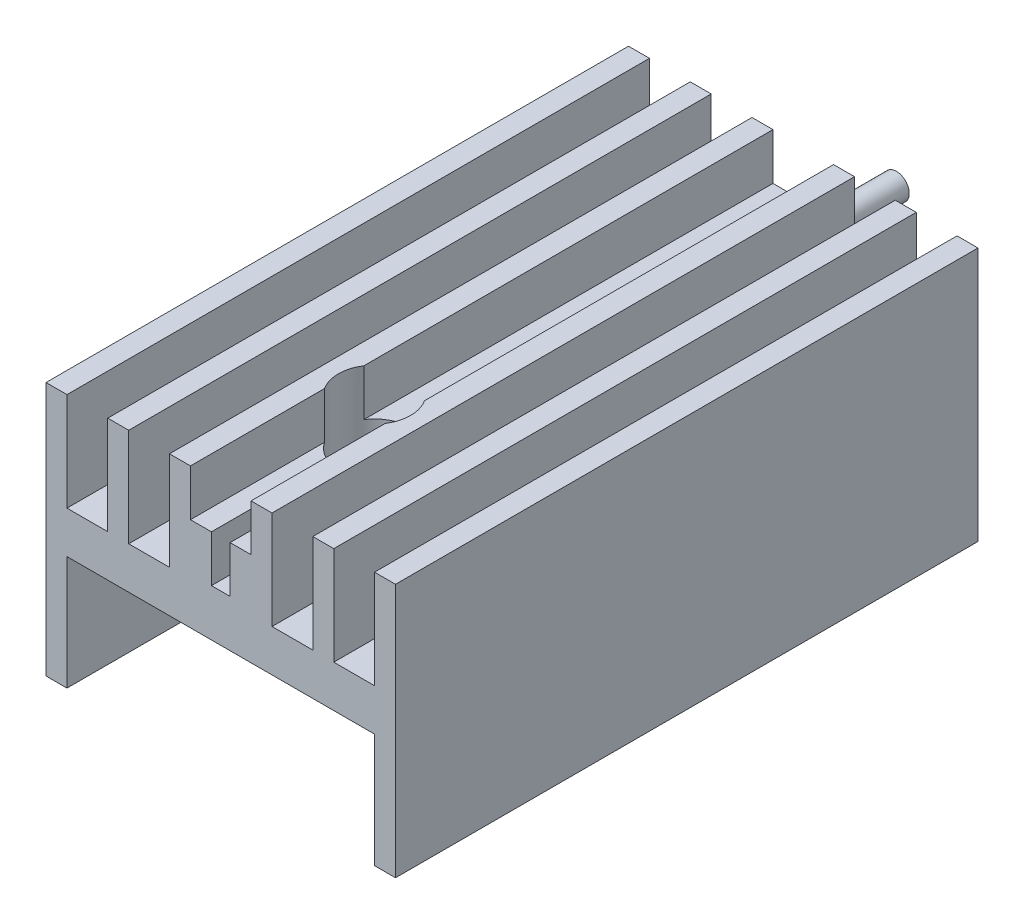
SolidWorks part; units mm, degrees
ref_plane "Front Plane" through (0, 0, 0) normal (0, 0, 1) x (1, 0, 0)
ref_plane "Top Plane" through (0, 0, 0) normal (0, 1, 0) x (1, 0, 0)
ref_plane "Right Plane" through (0, 0, 0) normal (1, 0, 0) x (0, 0, -1)
sketch "Sketch2" plane through (0, 0, 0) normal (0, 0, 1) x (1, 0, 0)
  line L0 (0, 16.15) -> (0, -13.7214) construction
  line L1 (-10.9286, 0) -> (8.9371, 0) construction
  line L2 (-6.6, -0.565) -> (-6.6, -5.455)
  line L3 (-6.6, -5.455) -> (-7.5, -5.455)
  line L4 (-7.5, -5.455) -> (-7.5, 5.455)
  line L5 (-7.5, 5.455) -> (-6.6, 5.455)
  line L6 (-6.6, 5.455) -> (-6.6, 1.235)
  line L7 (-6.6, 1.235) -> (-4.85, 1.235)
  line L8 (-4.85, 1.235) -> (-4.85, 5.455)
  line L9 (-4.85, 5.455) -> (-3.95, 5.455)
  line L10 (-3.95, 5.455) -> (-3.95, 1.235)
  line L11 (-3.95, 1.235) -> (-2.2, 1.235)
  line L12 (-2.2, 1.235) -> (-2.2, 5.455)
  line L13 (-2.2, 5.455) -> (-1.3, 5.455)
  line L14 (1.3, 5.455) -> (1.3, 3.455)
  line L15 (1.3, 3.455) -> (0.4, 3.455)
  line L16 (0.4, 3.455) -> (0.4, 1.455)
  line L17 (0.4, 1.455) -> (-0.4, 1.455)
  line L18 (-6.6, -0.565) -> (6.6, -0.565)
  line L19 (7.5, -5.455) -> (7.5, 5.455)
  line L20 (6.6, -5.455) -> (7.5, -5.455)
  line L21 (6.6, -0.565) -> (6.6, -5.455)
  line L22 (-0.4, 3.455) -> (-0.4, 1.455)
  line L23 (-1.3, 3.455) -> (-0.4, 3.455)
  line L24 (-1.3, 5.455) -> (-1.3, 3.455)
  line L25 (2.2, 5.455) -> (1.3, 5.455)
  line L26 (2.2, 1.235) -> (2.2, 5.455)
  line L27 (3.95, 1.235) -> (2.2, 1.235)
  line L28 (4.85, 5.455) -> (3.95, 5.455)
  line L29 (3.95, 5.455) -> (3.95, 1.235)
  line L30 (4.85, 1.235) -> (4.85, 5.455)
  line L31 (6.6, 1.235) -> (4.85, 1.235)
  line L32 (6.6, 5.455) -> (6.6, 1.235)
  line L33 (7.5, 5.455) -> (6.6, 5.455)
  point P23 (-7.5, 0)
  point P28 (0, 1.455)
  point P39 (0, -0.565)
  dimension "D1" = 1.75
  dimension "D2" = 1.75
  dimension "D3" = 10.91
  dimension "D4" = 0.9
  dimension "D5" = 4.22
  dimension "D6" = 15
  dimension "D7" = 0.9
  dimension "D8" = 0.9
  dimension "D9" = 0.9
  dimension "D10" = 1.8
  dimension "D11" = 2
  dimension "D12" = 2
extrude "Boss-Extrude1" add sketch "Sketch2" along normal mid plane 25
sketch "Sketch3" plane through (0, -0.565, 0) normal (0, -1, 0) x (1, 0, 0)
  line L0 (-6.6, 12.5) -> (6.6, 12.5) construction
  circle A0 centre (0, 5.9) radius 1.55
  dimension "D2" = 3.1
  dimension "D1" = 6.6
extrude "Cut-Extrude1" cut sketch "Sketch3" against normal blind 25
sketch "Sketch4" plane through (0, 0, -12.5) normal (0, 0, -1) x (-1, 0, 0)
  line L0 (-0.4, 1.455) -> (0.4, 1.455) construction
  circle A0 centre (0, 2.005) radius 0.55
  dimension "D1" = 1.1
extrude "Boss-Extrude4" add sketch "Sketch4" along normal blind 4 and the other way blind 6 separate body
